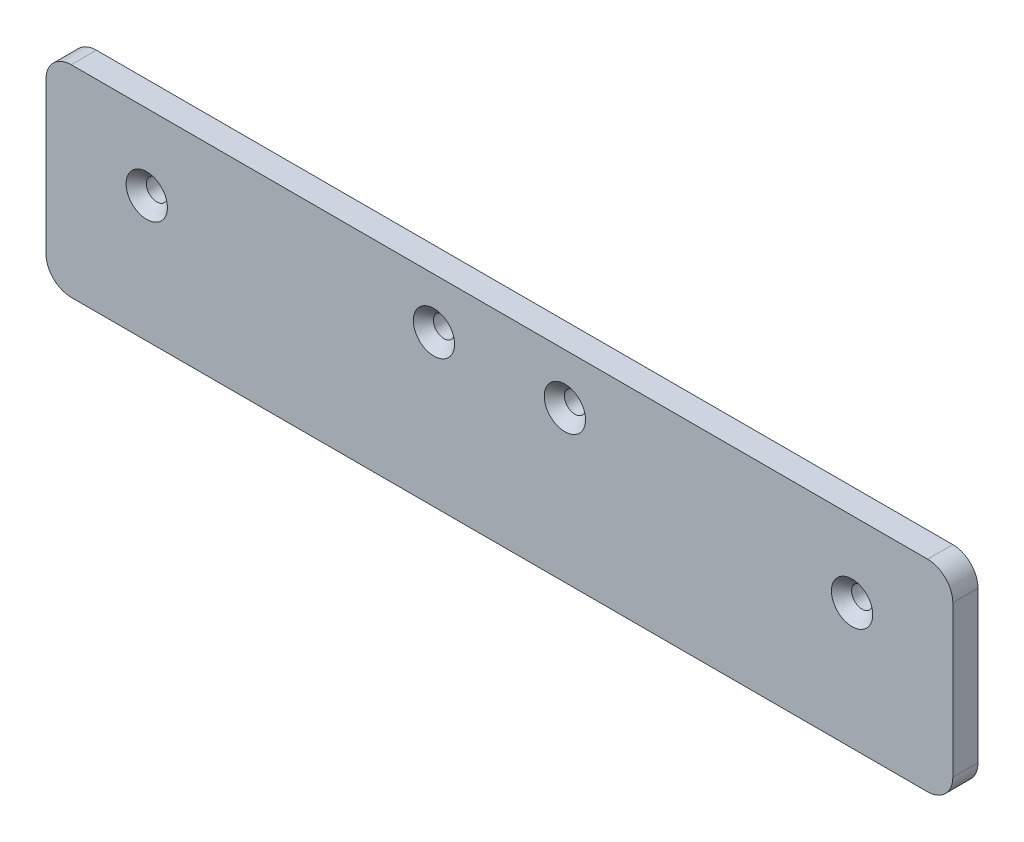
SolidWorks part; units mm, degrees
ref_plane "Płaszczyzna przednia" through (0, 0, 0) normal (0, 0, 1) x (1, 0, 0)
ref_plane "Płaszczyzna górna" through (0, 0, 0) normal (0, 1, 0) x (1, 0, 0)
ref_plane "Płaszczyzna prawa" through (0, 0, 0) normal (1, 0, 0) x (0, 0, -1)
sketch "Szkic1" plane through (0, 0, 0) normal (0, 0, 1) x (1, 0, 0)
  line L1 (-90, -20) -> (90, -20)
  line L2 (-90, -20) -> (-90, 20)
  line L3 (-90, 20) -> (90, 20)
  line L4 (90, -20) -> (90, 20)
  line L5 (-90, -20) -> (90, 20) construction
  line L6 (-90, 20) -> (90, -20) construction
  point P0 (0, 0)
  dimension "D1" = 40
  dimension "D2" = 180
extrude "Dodanie-wyciągnięcie1" add sketch "Szkic1" along normal blind 5
fillet "Zaokrąglenie1" radius 5 4 edges at (-90, 20, 2.5) (-90, -20, 2.5) (90, -20, 2.5) (90, 20, 2.5)
sketch "Szkic2" plane through (0, 0, 5) normal (0, 0, 1) x (1, 0, 0)
  line L0 (-90, 15) -> (-90, -15) construction
  line L1 (90, -15) -> (90, 15) construction
  line L2 (85, 20) -> (-85, 20) construction
  circle A0 centre (-70, 5) radius 2.1
  circle A1 centre (-13, 10) radius 2.1
  circle A2 centre (13, 10) radius 2.1
  circle A3 centre (70, 5) radius 2.1
  point P8 (0, 0)
  point P9 (0, 0)
  point P11 (0, 0)
  point P16 (0, 0)
  dimension "D1" = 26
  dimension "D4" = 20
  dimension "D6" = 4.2
  dimension "D7" = 10
  dimension "D2" = 13
  dimension "D3" = 20
  dimension "D5" = 15
extrude "Wytnij-wyciągnięcie1" cut sketch "Szkic2" against normal blind 5
chamfer "Sfazowanie1" distance 2 angle 45 4 edges at (72.1, 5, 5) (15.1, 10, 5) (-10.9, 10, 5) (-67.9, 5, 5)
